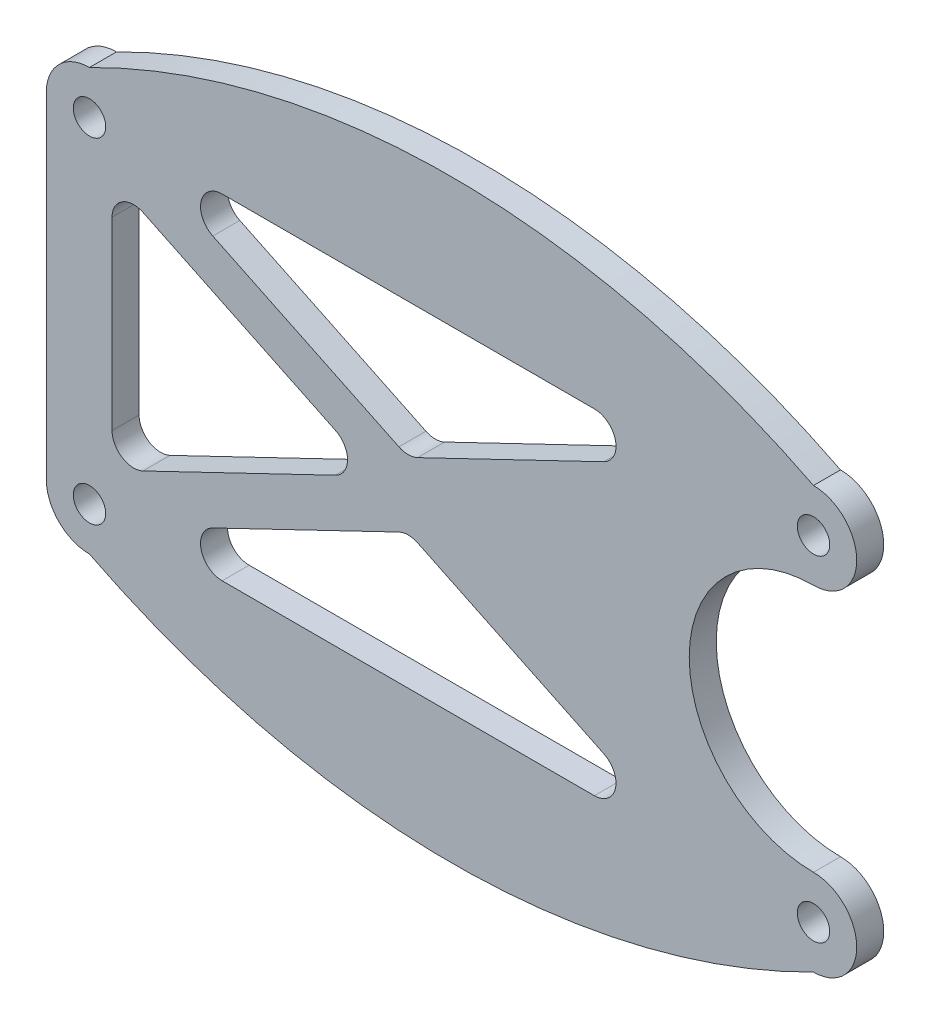
SolidWorks part; units mm, degrees
ref_plane "Alzado" through (0, 0, 0) normal (0, 0, 1) x (1, 0, 0)
ref_plane "Planta" through (0, 0, 0) normal (0, 1, 0) x (1, 0, 0)
ref_plane "Vista lateral" through (0, 0, 0) normal (1, 0, 0) x (0, 0, -1)
sketch "Croquis1" plane through (0, 0, 0) normal (0, 0, 1) x (1, 0, 0)
  circle A0 centre (-97.3181, 15.5) radius 1.5
  circle A1 centre (-97.3181, -15.5) radius 1.5
  circle A2 centre (-35.3181, -15.5) radius 1.5
  circle A3 centre (-35.3181, 15.5) radius 1.5
ref_plane "Plano1" through (0, 0, 0) normal (0, 0, 1) x (1, 0, 0)
sketch "Croquis2" plane through (0, 0, 0) normal (0, 0, 1) x (1, 0, 0)
  line L0 (-97.3181, 19.5) -> (-30.3181, 19.5)
  line L1 (-97.3181, -15.5) -> (-97.3181, 15.5) construction
  line L2 (-101.3181, 15.5) -> (-101.3181, -15.5)
  line L3 (-97.3181, 0) -> (-30.3181, 0) construction
  line L4 (-97.3181, -19.5) -> (-30.3181, -19.5)
  circle A0 centre (-97.3181, 15.5) radius 1.5
  circle A1 centre (-30.3181, 15.5) radius 1.5
  circle A2 centre (-30.3181, -15.5) radius 1.5
  circle A3 centre (-97.3181, -15.5) radius 1.5
  arc A4 (-97.3181, 19.5) -> (-101.3181, 15.5) centre (-97.3181, 15.5) ccw
  arc A5 (-30.3181, 11.5) -> (-30.3181, 19.5) centre (-30.3181, 15.5) ccw
  arc A6 (-30.3181, 11.5) -> (-30.3181, -11.5) centre (-30.3181, 0) ccw
  arc A7 (-30.3181, -11.5) -> (-30.3181, -19.5) centre (-30.3181, -15.5) cw
  arc A8 (-97.3181, -19.5) -> (-101.3181, -15.5) centre (-97.3181, -15.5) cw
  point P23 (-101.3181, 0)
  dimension "D4" = 3
  dimension "D1" = 4
  dimension "D2" = 67
extrude "Saliente-Extruir1" add sketch "Croquis2" along normal blind 2.5
sketch "Croquis3" plane through (0, 0, 2.5) normal (0, 0, 1) x (1, 0, 0)
  line L0 (-101.3181, 0) -> (-34.3181, 0) construction
  line L1 (-101.3181, 15.5) -> (-101.3181, -15.5) construction
  line L2 (-34.3181, 15.5) -> (-34.3181, -15.5) construction
  line L3 (-67.8181, 0) -> (-67.8181, 3) construction
  line L4 (-41.8181, 0) -> (-41.8181, 19.5) construction
  line L5 (-30.3181, 19.5) -> (-97.3181, 19.5) construction
  line L6 (-67.8181, 3) -> (-41.8181, 15.5)
  line L7 (-41.8181, 15.5) -> (-93.8181, 15.5)
  line L8 (-67.8181, 15.5) -> (-67.8181, 3) construction
  line L9 (-67.8181, 3) -> (-93.8181, 15.5)
  line L10 (-67.8181, -3) -> (-93.8181, -15.5)
  line L11 (-41.8181, -15.5) -> (-93.8181, -15.5)
  line L12 (-67.8181, -3) -> (-41.8181, -15.5)
  line L13 (-70.8181, 0) -> (-95.2287, 11.7359)
  line L14 (-95.2287, 11.7359) -> (-95.2287, -11.7359)
  line L15 (-70.8181, 0) -> (-95.2287, -11.7359)
  arc A1 (-30.3181, 11.5) -> (-30.3181, 19.5) centre (-30.3181, 15.5) ccw construction
  arc A2 (-30.3181, -19.5) -> (-30.3181, -11.5) centre (-30.3181, -15.5) ccw construction
  arc A3 (-30.3181, 11.5) -> (-30.3181, -11.5) centre (-30.3181, 0) ccw construction
  point P32 (-95.2287, 0)
  dimension "D1" = 3
  dimension "D2" = 3
  dimension "D3" = 4
extrude "Cortar-Extruir1" cut sketch "Croquis3" against normal up to vertex (2.5 mm away)
fillet "Redondeo1" radius 2 9 edges at (-93.8181, 15.5, 1.25) (-67.8181, 3, 1.25) (-67.8181, -3, 1.25) (-41.8181, -15.5, 1.25) (-41.8181, 15.5, 1.25) (-70.8181, 0, 1.25) (-95.2287, -11.7359, 1.25) (-95.2287, 11.7359, 1.25) (-93.8181, -15.5, 1.25)
sketch "Croquis5" plane through (0, 0, 2.5) normal (0, 0, 1) x (1, 0, 0)
  line L4 (-97.3181, 19.5) -> (-30.3181, 19.5)
  line L5 (-63.8181, 19.5) -> (-63.8181, 27.5) construction
  line L6 (-101.3181, 0) -> (-41.8181, 0) construction
  line L7 (-101.3181, 15.5) -> (-101.3181, -15.5) construction
  line L8 (-63.8181, -19.5) -> (-63.8181, -27.5) construction
  line L9 (-97.3181, -19.5) -> (-30.3181, -19.5)
  arc A5 (-97.3181, 19.5) -> (-30.3181, 19.5) centre (-63.8181, -46.6406) cw
  arc A8 (-30.3181, 11.5) -> (-30.3181, -11.5) centre (-30.3181, 0) ccw construction
  arc A9 (-97.3181, -19.5) -> (-30.3181, -19.5) centre (-63.8181, 46.6406) ccw
  dimension "D1" = 8
extrude "Saliente-Extruir2" add sketch "Croquis5" against normal up to vertex (2.5 mm away)
sketch "Croquis6" plane through (0, 0, 2.5) normal (0, 0, 1) x (1, 0, 0)
  line L2 (-101.3181, 15.5) -> (-101.3181, -15.5)
  line L3 (-101.3181, 15.5) -> (-101.3181, -15.5)
  circle A10 centre (-97.3181, 15.5) radius 1.5
  circle A11 centre (-30.3181, 15.5) radius 3.5924
  circle A12 centre (-30.3181, -15.5) radius 3.5924
  circle A13 centre (-97.3181, -15.5) radius 1.5
  arc A14 (-97.3181, 19.5) -> (-101.3181, 15.5) centre (-97.3181, 15.5) ccw
  arc A15 (-101.3181, -15.5) -> (-97.3181, -19.5) centre (-97.3181, -15.5) ccw
  arc A16 (-97.3181, -19.5) -> (-30.3181, -19.5) centre (-63.8181, 46.6406) ccw
  arc A17 (-30.3181, -19.5) -> (-30.3181, -11.5) centre (-30.3181, -15.5) ccw
  arc A18 (-30.3181, 11.5) -> (-30.3181, -11.5) centre (-30.3181, 0) ccw
  arc A19 (-30.3181, 11.5) -> (-30.3181, 19.5) centre (-30.3181, 15.5) ccw
  arc A20 (-30.3181, 19.5) -> (-97.3181, 19.5) centre (-63.8181, -46.6406) ccw
  arc A21 (-97.3181, 19.5) -> (-101.3181, 15.5) centre (-97.3181, 15.5) ccw
  arc A22 (-101.3181, -15.5) -> (-97.3181, -19.5) centre (-97.3181, -15.5) ccw
  arc A23 (-97.3181, -19.5) -> (-30.3181, -19.5) centre (-63.8181, 46.6406) ccw
  arc A24 (-30.3181, -19.5) -> (-30.3181, -11.5) centre (-30.3181, -15.5) ccw
  arc A25 (-30.3181, 11.5) -> (-30.3181, -11.5) centre (-30.3181, 0) ccw
  arc A26 (-30.3181, 11.5) -> (-30.3181, 19.5) centre (-30.3181, 15.5) ccw
  arc A27 (-30.3181, 19.5) -> (-97.3181, 19.5) centre (-63.8181, -46.6406) ccw
  dimension "D1" = 0
